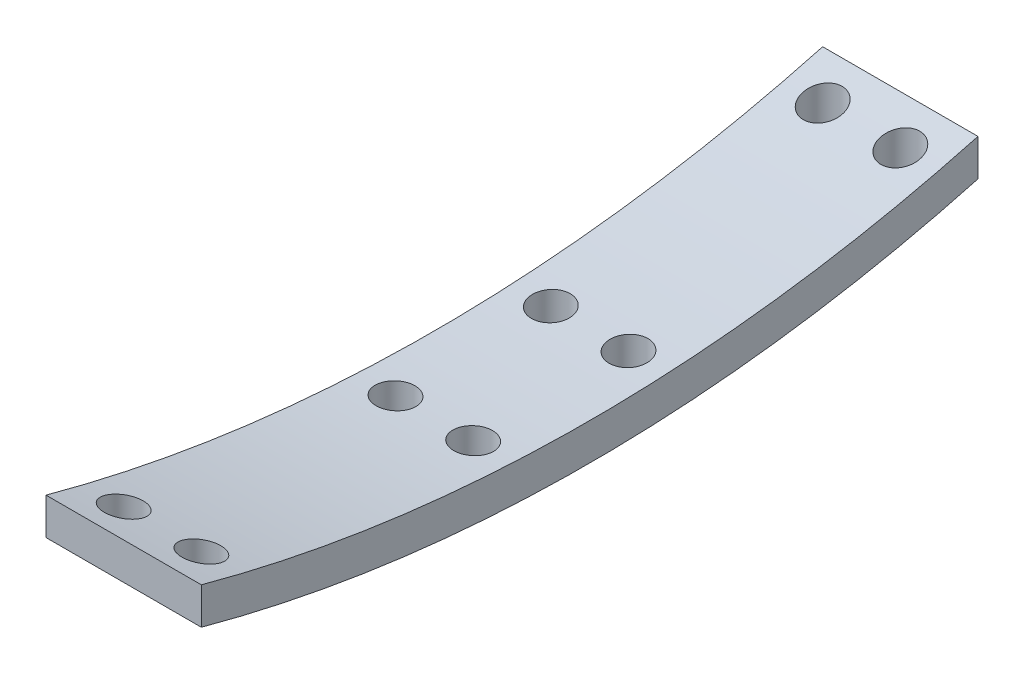
SolidWorks part; units mm, degrees
ref_plane "Front Plane" through (0, 0, 0) normal (0, 0, 1) x (1, 0, 0)
ref_plane "Top Plane" through (0, 0, 0) normal (0, 1, 0) x (1, 0, 0)
ref_plane "Right Plane" through (0, 0, 0) normal (1, 0, 0) x (0, 0, -1)
sketch "Sketch3" plane through (0, 0, 0) normal (1, 0, 0) x (0, 0, -1)
  line L0 (-8.3933, 1.9614) -> (-8.3933, -4.052)
  line L6 (-8.3933, -4.3886) -> (-8.3933, 1.9614)
  line L8 (232.9067, -4.3886) -> (232.9067, 1.9614)
  line L9 (232.9067, -4.052) -> (232.9067, 1.9614)
  arc A2 (-8.3933, 1.9614) -> (232.9067, 1.9614) centre (112.2567, 210.9333) ccw
  arc A3 (-8.3933, -4.052) -> (232.9067, -4.052) centre (112.2567, 204.9199) ccw
  dimension "D1" = 6.35
  dimension "D2" = 241.3
extrude "Boss-Extrude4" add sketch "Sketch3" along normal blind 304.8 contours L0 A3 L8 A2
ref_plane "Plane1" through (0, 1.9614, 0) normal (0, 1, 0) x (1, 0, 0)
sketch "Sketch4" plane through (0, 1.9614, 0) normal (0, 1, 0) x (1, 0, 0)
  line L0 (0, 112.2567) -> (28.689, 112.2567)
  line L2 (0, 232.9067) -> (0, -8.3933) construction
  line L3 (28.689, 175.7567) -> (28.689, 48.7567)
  line L4 (28.689, 48.7567) -> (28.689, -8.3933)
  line L5 (304.8, -8.3933) -> (0, -8.3933) construction
  line L7 (28.689, 175.7567) -> (54.089, 175.7567)
  line L8 (28.689, 175.7567) -> (28.689, 48.7567)
  line L9 (28.689, 48.7567) -> (54.089, 48.7567)
  line L10 (54.089, 175.7567) -> (54.089, 48.7567)
  point P12 (0, 0)
  point P13 (28.689, 112.2567)
  point P14 (218.6021, 442.5723)
  dimension "D3" = 25.4
  dimension "D4" = 127
extrude "Cut-Extrude2" cut sketch "Sketch4" against normal blind 150 flip side to cut contours L8 L7 L10 L9
sketch "Sketch5" plane through (0, 1.9614, 0) normal (0, 1, 0) x (1, 0, 0)
  circle A0 centre (47.739, 169.4067) radius 3.175
  circle A1 centre (35.039, 169.4067) radius 3.175
  circle A2 centre (35.039, 55.1067) radius 3.175
  circle A3 centre (47.739, 55.1067) radius 3.175
sketch "Sketch6" plane through (0, 1.9614, 0) normal (0, 1, 0) x (1, 0, 0)
  circle A0 centre (35.039, 124.9567) radius 3.175
  circle A1 centre (47.739, 124.9567) radius 3.175
  circle A2 centre (35.039, 99.5567) radius 3.175
  circle A3 centre (47.739, 99.5567) radius 3.175
extrude "Cut-Extrude4" cut sketch "Sketch6" against normal blind 150
extrude "Cut-Extrude5" cut sketch "Sketch5" against normal blind 150
